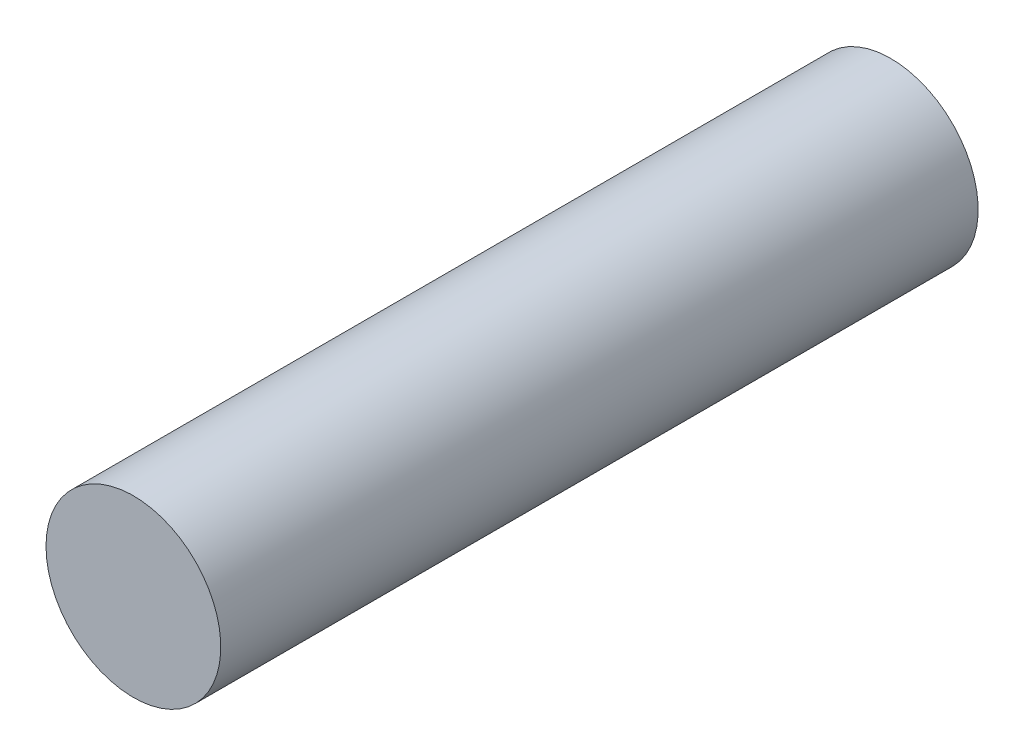
SolidWorks part; units mm, degrees
ref_plane "Front Plane" through (0, 0, 0) normal (0, 0, 1) x (1, 0, 0)
ref_plane "Top Plane" through (0, 0, 0) normal (0, 1, 0) x (1, 0, 0)
ref_plane "Right Plane" through (0, 0, 0) normal (1, 0, 0) x (0, 0, -1)
sketch "Sketch1" plane through (0, 0, 0) normal (0, 0, 1) x (1, 0, 0)
  circle A0 centre (0, 0) radius 1.5
  dimension "D1" = 3
extrude "Boss-Extrude1" add sketch "Sketch1" along normal blind 13
